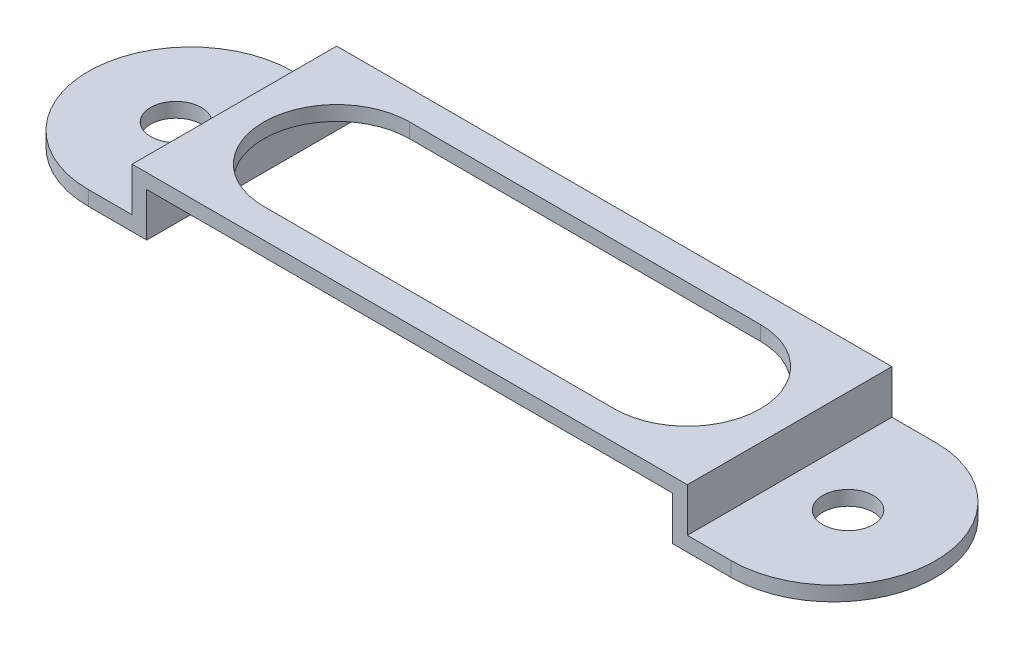
SolidWorks part; units mm, degrees
ref_plane "Front Plane" through (0, 0, 0) normal (0, 0, 1) x (1, 0, 0)
ref_plane "Top Plane" through (0, 0, 0) normal (0, 1, 0) x (1, 0, 0)
ref_plane "Right Plane" through (0, 0, 0) normal (1, 0, 0) x (0, 0, -1)
sketch "Sketch2" plane through (0, 0, 0) normal (0, 1, 0) x (1, 0, 0)
  line L0 (0, 0) -> (69.85, 0) construction
  line L1 (0, 11.1125) -> (69.85, 11.1125)
  line L2 (0, -11.1125) -> (69.85, -11.1125)
  line L3 (15.875, 0) -> (53.975, 0) construction
  line L4 (15.875, 7.9375) -> (53.975, 7.9375)
  line L5 (15.875, -7.9375) -> (53.975, -7.9375)
  arc A0 (0, 11.1125) -> (0, -11.1125) centre (0, 0) ccw
  arc A1 (69.85, -11.1125) -> (69.85, 11.1125) centre (69.85, 0) ccw
  arc A2 (15.875, 7.9375) -> (15.875, -7.9375) centre (15.875, 0) ccw
  arc A3 (53.975, -7.9375) -> (53.975, 7.9375) centre (53.975, 0) ccw
  point P3 (34.925, 0)
  point P10 (34.925, 0)
  dimension "D2" = 11.1125
  dimension "D4" = 7.9375
  dimension "D1" = 69.85
  dimension "D3" = 38.1
extrude "Boss-Extrude1" add sketch "Sketch2" along normal blind 6.35
sketch "Sketch3" plane through (0, 6.35, 0) normal (0, 1, 0) x (1, 0, 0)
  arc A0 (0, 11.1125) -> (0, -11.1125) centre (0, 0) ccw construction
  arc A1 (69.85, -11.1125) -> (69.85, 11.1125) centre (69.85, 0) ccw construction
  point P0 (-1.5875, 0)
  point P1 (71.4375, 0)
  dimension "D1" = 1.5875
  dimension "D2" = 1.5875
sketch "Sketch6" plane through (0, 0, -11.1125) normal (0, 0, -1) x (-1, 0, 0)
  line L0 (-6.35, 0) -> (-6.35, 4.7625)
  line L2 (-6.35, 4.7625) -> (-63.5, 4.7625)
  line L4 (-63.5, 4.7625) -> (-63.5, 0)
  line L7 (-80.9625, 1.5875) -> (-65.0875, 1.5875)
  line L8 (-65.0875, 1.5875) -> (-65.0875, 6.35)
  line L10 (-4.7625, 6.35) -> (-4.7625, 1.5875)
  line L11 (-4.7625, 1.5875) -> (11.1125, 1.5875)
  line L14 (11.1125, 6.35) -> (0, 6.35) construction
  line L15 (11.1125, 0) -> (11.1125, 6.35) construction
  line L16 (-80.9625, 6.35) -> (-80.9625, 0) construction
  line L17 (-69.85, 6.35) -> (-80.9625, 6.35) construction
  line L18 (-69.85, 0) -> (0, 0) construction
  line L19 (11.1125, 6.35) -> (-4.7625, 6.35)
  line L20 (-65.0875, 6.35) -> (-80.9625, 6.35)
  line L21 (-63.5, 0) -> (-6.35, 0)
  line L22 (-80.9625, 1.5875) -> (-80.9625, 6.35)
  line L23 (11.1125, 6.35) -> (11.1125, 1.5875)
  line L25 (0, 0) -> (11.1125, 0) construction
  line L26 (-69.85, 6.35) -> (0, 6.35) construction
  point P6 (-69.85, 3.175)
  point P7 (0, 0)
  point P19 (-6.35, 2.3813)
  point P22 (0, 0)
  point P30 (0, 0)
  dimension "D1" = 57.15
  dimension "D2" = 1.5875
  dimension "D3" = 1.5875
  dimension "D4" = 1.5875
  dimension "D5" = 1.5875
  dimension "D6" = 15.875
  dimension "D7" = 1.5875
extrude "Cut-Extrude1" cut sketch "Sketch6" against normal through all
hole_wizard "M5 Clearance Hole1" positions "Sketch7" profile "Sketch8" hole size "M5" standard "ANSI Metric" end condition through all
sketch "Sketch7" plane through (0, 1.5875, 0) normal (0, 1, 0) x (1, 0, 0)
  point P0 (-1.5875, 0)
  point P3 (71.4375, 0)
sketch "Sketch8" plane through (-1.5875, 1.5875, 0) normal (1, 0, 0) x (0, 0, 1)
  line L0 (0, 0) -> (0, 1.5875)
  line L1 (0, 1.5875) -> (2.75, 1.5875)
  line L2 (2.75, 1.5875) -> (2.75, 0)
  line L5 (2.75, 0) -> (0, 0)
  line L11 (0, -6.35) -> (0, 107.95) construction
  dimension "Thru Hole Dia." = 5.5
  dimension "Thru Hole Depth" = 1.5875
